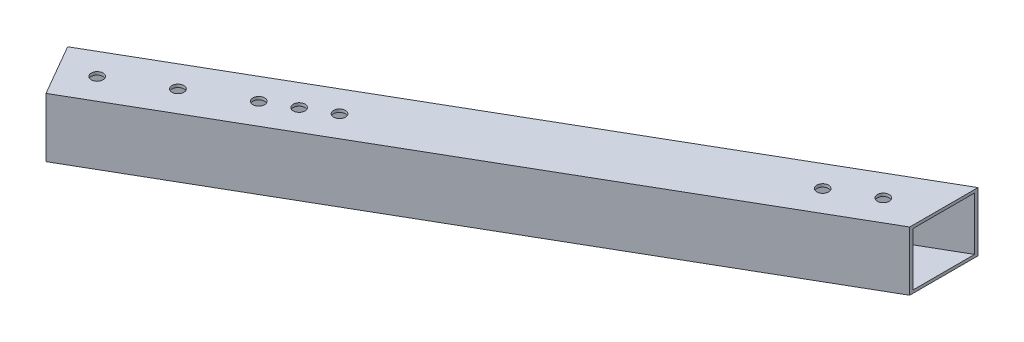
SolidWorks part; units mm, degrees
ref_plane "前视基准面" through (0, 0, 0) normal (0, 0, 1) x (1, 0, 0)
ref_plane "上视基准面" through (0, 0, 0) normal (0, 1, 0) x (1, 0, 0)
ref_plane "右视基准面" through (0, 0, 0) normal (1, 0, 0) x (0, 0, -1)
sketch "草图1" plane through (0, 0, 0) normal (0, 1, 0) x (1, 0, 0)
  line L0 (98.0362, 64.9252) -> (98.0362, 41.8312)
  line L1 (98.0362, 41.8312) -> (-87.1709, -65.0982)
  line L2 (-87.1709, -65.0982) -> (-97.1709, -47.7777)
  line L3 (-97.1709, -47.7777) -> (98.0362, 64.9252)
  circle A0 centre (-83.4815, -51.4867) radius 2
  circle A1 centre (-66.161, -41.4867) radius 2
  circle A2 centre (-48.8696, -31.438) radius 2
  circle A3 centre (-40.2094, -26.438) radius 2
  circle A4 centre (-31.5491, -21.438) radius 2
  circle A5 centre (72.0555, 38.3782) radius 2
  circle A6 centre (85.0458, 45.8782) radius 2
extrude "凸台-拉伸1" add sketch "草图1" along normal blind 20
sketch "草图2" plane through (-93.5665, 0, 54.0207) normal (-0.866, 0, 0.5) x (0.5, 0, 0.866)
  line L0 (2.7913, 0) -> (2.7913, 20) construction
  line L1 (-7.2087, 0) -> (12.7913, 0) construction
  line L2 (-7.2087, 20) -> (12.7913, 20) construction
  line L4 (-6.2087, 19) -> (11.7913, 19)
  line L5 (-6.2087, 19) -> (-6.2087, 1)
  line L6 (-6.2087, 1) -> (11.7913, 1)
  line L7 (11.7913, 19) -> (11.7913, 1)
  line L8 (2.7913, 1) -> (2.7913, 19) construction
  line L9 (-6.2087, 10) -> (11.7913, 10) construction
  point P6 (2.7913, 10)
  dimension "D1" = 18
  dimension "D2" = 18
extrude "切除-拉伸1" cut sketch "草图2" against normal through all
